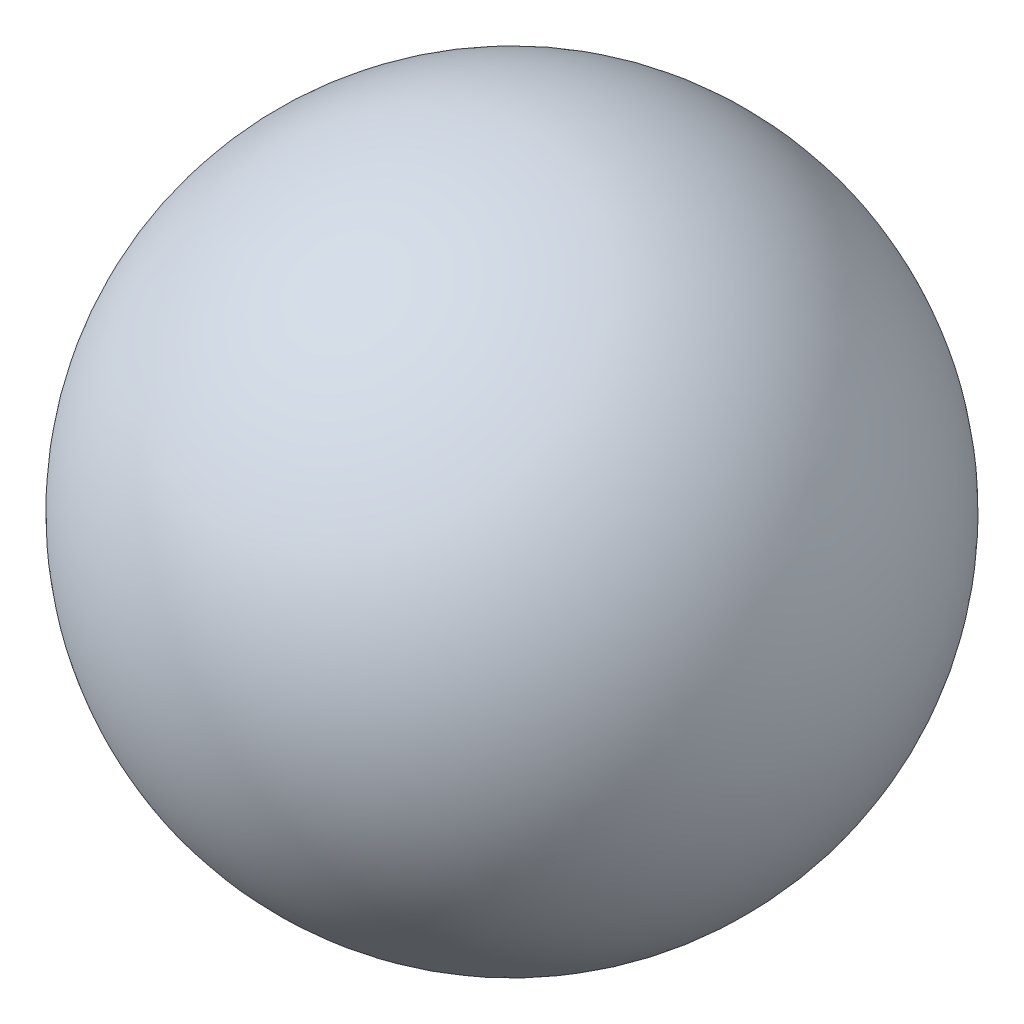
SolidWorks part; units mm, degrees
ref_plane "前基準面" through (0, 0, 0) normal (0, 0, 1) x (1, 0, 0)
ref_plane "上基準面" through (0, 0, 0) normal (0, 1, 0) x (1, 0, 0)
ref_plane "右基準面" through (0, 0, 0) normal (1, 0, 0) x (0, 0, -1)
sketch "草圖1" plane through (0, 0, 0) normal (0, 1, 0) x (1, 0, 0)
  line L0 (0, 44.87) -> (0, -44.87) construction
  line L1 (0, -44.87) -> (0, 44.87)
  arc A0 (0, -44.87) -> (0, 44.87) centre (0, 0) cw
revolve "旋轉1" add sketch "草圖1" angle 360 about L0
